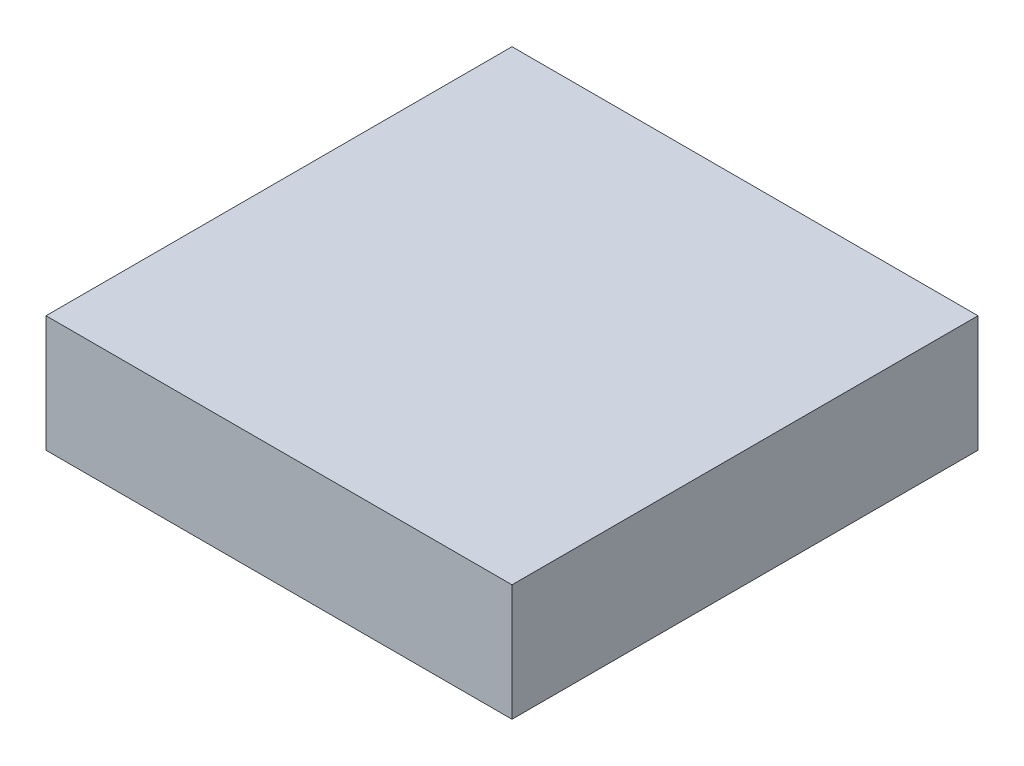
SolidWorks part; units mm, degrees
material "Alloy Steel"
ref_plane "Front Plane" through (0, 0, 0) normal (0, 0, 1) x (1, 0, 0)
ref_plane "Top Plane" through (0, 0, 0) normal (0, 1, 0) x (1, 0, 0)
ref_plane "Right Plane" through (0, 0, 0) normal (1, 0, 0) x (0, 0, -1)
sketch "Sketch1" plane through (0, 0, 0) normal (0, 1, 0) x (1, 0, 0)
  line L1 (-50.8, -50.8) -> (50.8, -50.8)
  line L2 (-50.8, -50.8) -> (-50.8, 50.8)
  line L3 (-50.8, 50.8) -> (50.8, 50.8)
  line L4 (50.8, -50.8) -> (50.8, 50.8)
  line L5 (-50.8, -50.8) -> (50.8, 50.8) construction
  line L6 (-50.8, 50.8) -> (50.8, -50.8) construction
  point P0 (0, 0)
extrude "Boss-Extrude1" add sketch "Sketch1" along normal blind 25.4
